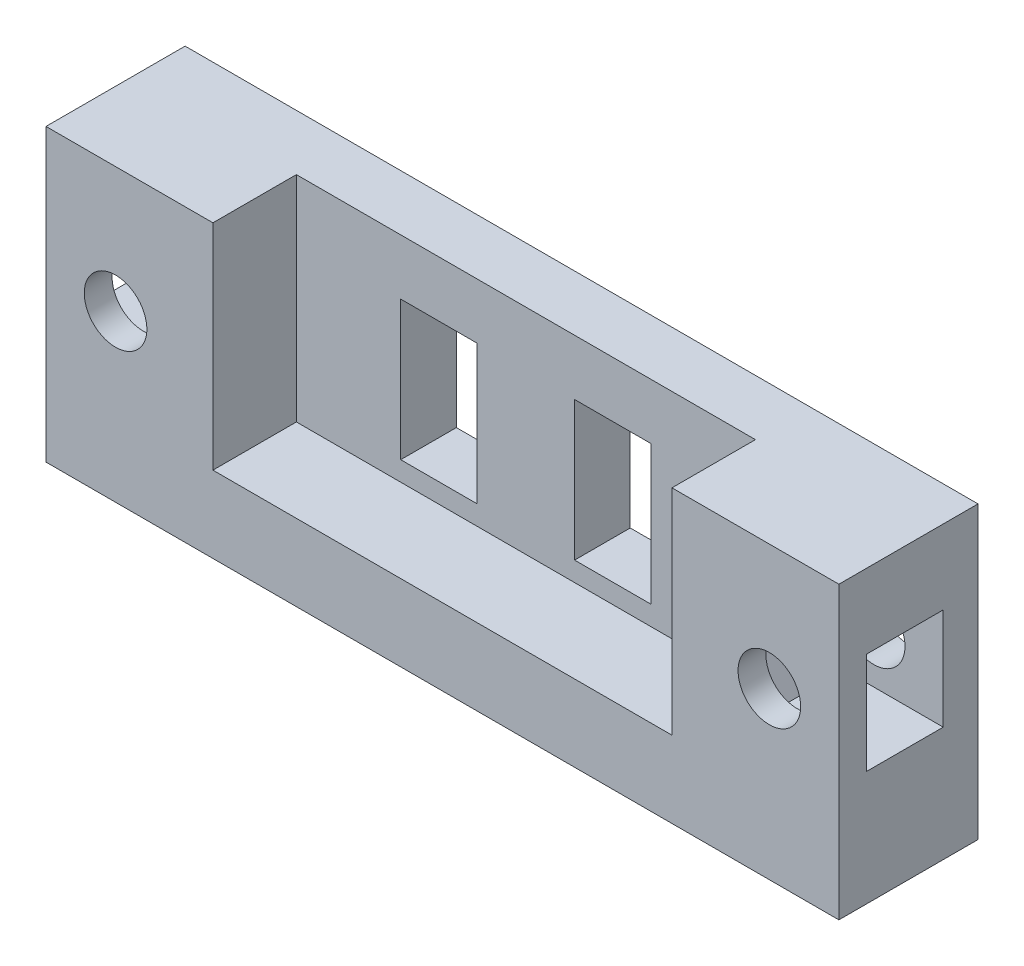
SolidWorks part; units mm, degrees
ref_plane "Plan de face" through (0, 0, 0) normal (0, 0, 1) x (1, 0, 0)
ref_plane "Plan de dessus" through (0, 0, 0) normal (0, 1, 0) x (1, 0, 0)
ref_plane "Plan de droite" through (0, 0, 0) normal (1, 0, 0) x (0, 0, -1)
sketch "Esquisse1" plane through (0, 0, 0) normal (0, 0, 1) x (1, 0, 0)
  line L1 (0, 0) -> (57, 0)
  line L2 (0, 0) -> (0, -20.9)
  line L3 (0, -20.9) -> (57, -20.9)
  line L4 (57, 0) -> (57, -20.9)
  line L5 (37.5, -4) -> (32, -4)
  line L6 (37.5, -4) -> (37.5, -14)
  line L7 (37.5, -14) -> (32, -14)
  line L8 (32, -4) -> (32, -14)
  line L9 (25, -4) -> (19.5, -4)
  line L10 (25, -4) -> (25, -14)
  line L11 (25, -14) -> (19.5, -14)
  line L12 (19.5, -4) -> (19.5, -14)
  circle A0 centre (5, -9) radius 2.25
  circle A1 centre (52, -9) radius 2.25
  point P17 (34.75, -4)
  point P18 (28.5, 0)
  dimension "D3" = 4.5
  dimension "D4" = 4.5
  dimension "D7" = 9
  dimension "D1" = 20.9
  dimension "D2" = 57
  dimension "D5" = 5
  dimension "D6" = 5
  dimension "D8" = 9
  dimension "D9" = 5.5
  dimension "D10" = 5.5
  dimension "D11" = 10
  dimension "D12" = 10
  dimension "D13" = 4
  dimension "D14" = 4
  dimension "D15" = 3.5
  dimension "D16" = 3.5
extrude "Boss.-Extru.2" add sketch "Esquisse1" along normal blind 4
sketch "Esquisse2" plane through (0, 0, 4) normal (0, 0, 1) x (1, 0, 0)
  line L0 (57, 0) -> (0, 0) construction
  line L1 (57, 0) -> (45, 0)
  line L2 (57, 0) -> (57, -20.9)
  line L3 (57, -20.9) -> (45, -20.9)
  line L4 (45, 0) -> (45, -20.9)
  line L5 (57, -20.9) -> (57, 0) construction
  line L6 (0, -20.9) -> (57, -20.9) construction
  line L8 (45, -20.9) -> (28.5, -20.9)
  line L9 (45, -20.9) -> (45, -15.4)
  line L10 (45, -15.4) -> (28.5, -15.4)
  line L11 (28.5, -20.9) -> (28.5, -15.4)
  point P13 (28.5, -20.9)
  line M5 (0, -20.9) -> (57, -20.9)
  line M6 (57, -20.9) -> (57, 0)
  line M7 (57, 0) -> (0, 0)
  circle M8 centre (52, -9) radius 2.25
  dimension "D1" = 12
  dimension "D2" = 0
  dimension "D3" = 5.5
extrude "Boss.-Extru.3" add sketch "Esquisse2" along normal blind 6 contours L11 L4 L10 M5 | L4 M7 M5 M6 M8
sketch "Esquisse4" plane through (0, 0, 10) normal (0, 0, 1) x (1, 0, 0)
  line L0 (54.1073, -5.35) -> (57, -5.35)
  line L1 (47.7853, -9) -> (49.8927, -12.65)
  line L2 (49.8927, -12.65) -> (54.1073, -12.65)
  line L3 (54.1073, -12.65) -> (56.2147, -9)
  line L4 (56.2147, -9) -> (54.1073, -5.35)
  line L5 (54.1073, -5.35) -> (49.8927, -5.35)
  line L6 (49.8927, -5.35) -> (47.7853, -9)
  line L8 (54.1073, -12.65) -> (57, -12.65)
  line L10 (57, -5.35) -> (57, -12.65)
  line L11 (45, 0) -> (45, -15.4) construction
  circle A0 centre (52, -9) radius 3.65 construction
  dimension "D1" = 90
  dimension "D2" = 7.3
extrude "Enlèv. mat.-Extru.2" cut sketch "Esquisse4" against normal blind 5.5 from offset 2 offset against normal yes
ref_plane "Plan1" through (28.5, 0, 0) normal (1, 0, 0) x (0, 0, -1)
mirror "Symétrie3" about plane through (28.5, 0, 0) normal (1, 0, 0) of "Boss.-Extru.3", "Enlèv. mat.-Extru.2"
